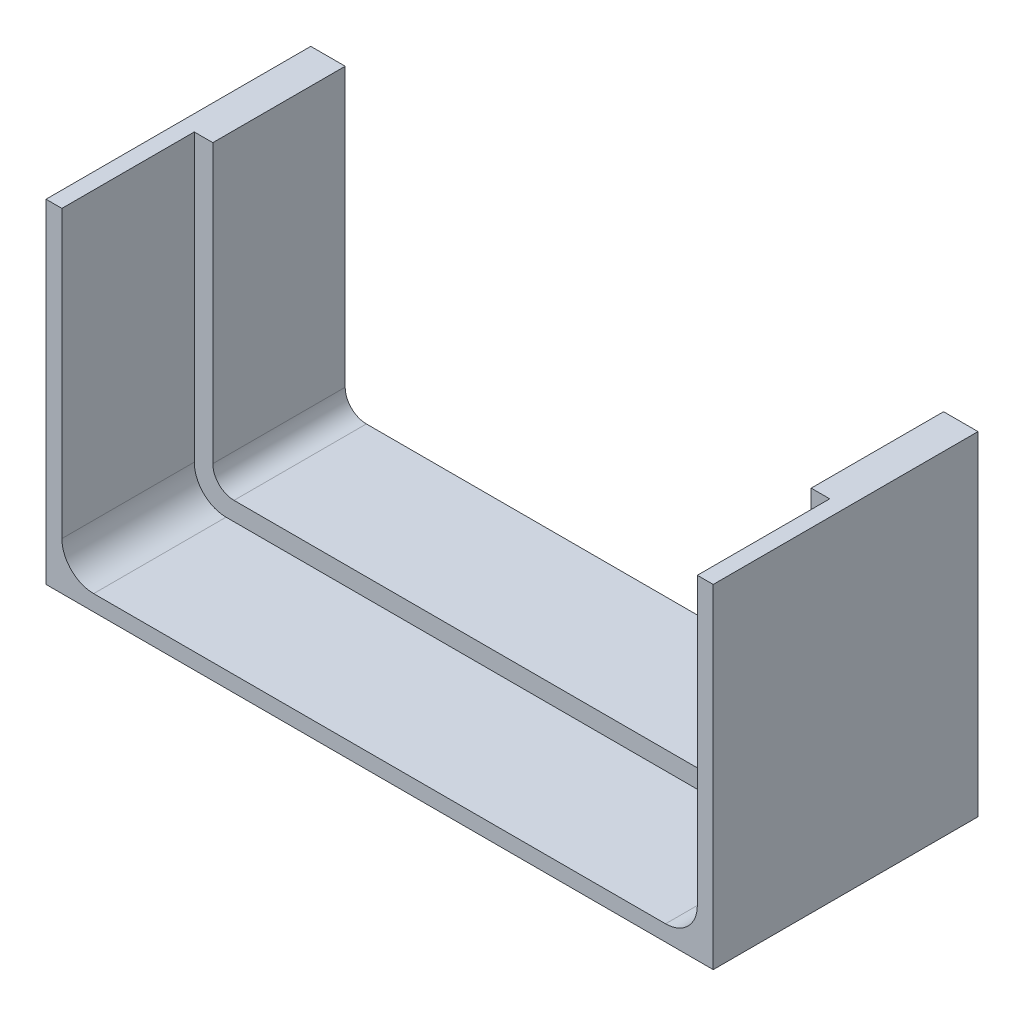
SolidWorks part; units mm, degrees
ref_plane "Front Plane" through (0, 0, 0) normal (0, 0, 1) x (1, 0, 0)
ref_plane "Top Plane" through (0, 0, 0) normal (0, 1, 0) x (1, 0, 0)
ref_plane "Right Plane" through (0, 0, 0) normal (1, 0, 0) x (0, 0, -1)
sketch "Sketch2" plane through (0, 0, 0) normal (0, 0, 1) x (1, 0, 0)
  line L0 (-63, 0) -> (-60, 0)
  line L1 (-59.5, -59.5) -> (59.5, -59.5) construction
  line L2 (-59.5, -59.5) -> (-59.5, 59.5) construction
  line L3 (-59.5, 59.5) -> (59.5, 59.5) construction
  line L4 (59.5, -59.5) -> (59.5, 59.5) construction
  line L5 (0, 59.5) -> (0, -59.5) construction
  line L6 (-59.5, 0) -> (59.5, 0) construction
  line L7 (-60, 0) -> (-60, -60)
  line L8 (-60, -60) -> (60, -60)
  line L9 (60, -60) -> (60, 0)
  line L10 (60, 0) -> (63, 0)
  line L11 (63, 0) -> (63, -63)
  line L12 (63, -63) -> (-63, -63)
  line L13 (-63, -63) -> (-63, 0)
  line L14 (-60, 0) -> (-59.5, 0) construction
  line L15 (59.5, 0) -> (60, 0) construction
  line L16 (0, -59.5) -> (0, -60) construction
  line L17 (0, -60) -> (0, -63) construction
  point P0 (0, 0)
  dimension "D1" = 119
  dimension "D2" = 3
  dimension "D3" = 0.5
extrude "Boss-Extrude1" add sketch "Sketch2" along normal blind 25
fillet "Fillet1" radius 6 2 edges at (60, -60, 12.5) (-60, -60, 12.5)
sketch "Sketch3" plane through (0, 0, 0) normal (0, 0, -1) x (-1, 0, 0)
  line L0 (63, -63) -> (63, 0) construction
  line L1 (-63, 0) -> (-63, -63) construction
  line L2 (-63, -63) -> (63, -63) construction
  line L3 (63, -63) -> (63, 0)
  line L4 (-63, 0) -> (-63, -63)
  line L5 (-63, -63) -> (63, -63)
  line L6 (63, 0) -> (56.5, 0)
  line L7 (59.5, 0) -> (-59.5, 0) construction
  line L8 (56.5, 0) -> (56.5, -56.5)
  line L9 (56.5, -56.5) -> (-56.5, -56.5)
  line L10 (-56.5, -56.5) -> (-56.5, 0)
  line L11 (-56.5, 0) -> (-63, 0)
  line L12 (0, -56.5) -> (0, -63) construction
  line L13 (59.5, -59.5) -> (59.5, 59.5) construction
  line L15 (-52.5, 52.5) -> (52.5, 52.5) construction
  line L16 (-52.5, 52.5) -> (-52.5, -52.5) construction
  line L17 (-52.5, -52.5) -> (52.5, -52.5) construction
  line L18 (52.5, 52.5) -> (52.5, -52.5) construction
  line L19 (0, -52.5) -> (0, 52.5) construction
  line L20 (-52.5, 0) -> (52.5, 0) construction
  circle A0 centre (52.5, -52.5) radius 3.5 construction
  circle A1 centre (-52.5, -52.5) radius 3.5 construction
  point P14 (0, 0)
  dimension "D2" = 7
  dimension "D1" = 3
  dimension "D3" = 105
extrude "Boss-Extrude2" add sketch "Sketch3" along normal blind 25
fillet "Fillet2" radius 4 2 edges at (56.5, -56.5, -12.5) (-56.5, -56.5, -12.5)
